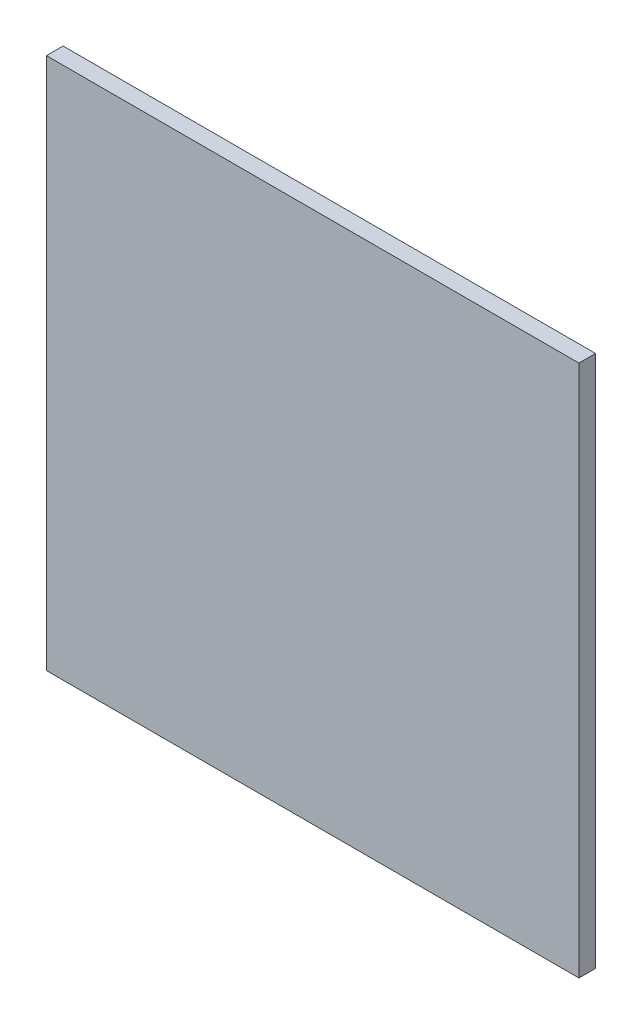
SolidWorks part; units mm, degrees
ref_plane "Alzado" through (0, 0, 0) normal (0, 0, 1) x (1, 0, 0)
ref_plane "Planta" through (0, 0, 0) normal (0, 1, 0) x (1, 0, 0)
ref_plane "Vista lateral" through (0, 0, 0) normal (1, 0, 0) x (0, 0, -1)
sketch "Croquis1" plane through (0, 0, 0) normal (0, 0, 1) x (1, 0, 0)
  line L1 (-210, 110) -> (110, 110)
  line L2 (-210, 110) -> (-210, -210)
  line L3 (-210, -210) -> (110, -210)
  line L4 (110, 110) -> (110, -210)
  point P0 (0, 0)
  dimension "D1" = 110
  dimension "D4" = 110
  dimension "D2" = 320
  dimension "D3" = 320
extrude "Saliente-Extruir2" add sketch "Croquis1" along normal blind 10
sketch "Croquis2" plane through (0, 0, 0) normal (0, 0, 1) x (1, 0, 0)
  line L1 (30, 30) -> (-130, 30)
  line L2 (30, 30) -> (30, -130)
  line L3 (30, -130) -> (-130, -130)
  line L4 (-130, 30) -> (-130, -130)
  line L5 (110, -210) -> (110, 110) construction
  line L6 (-210, -210) -> (110, -210) construction
  point P0 (-55.304, -54.2189)
  point P5 (-50, 30)
  dimension "D1" = 160
  dimension "D2" = 160
  dimension "D3" = 80
  dimension "D4" = 80
extrude "Saliente-Extruir3" add sketch "Croquis2" against normal blind 58
sketch "Croquis3" plane through (0, 0, -58) normal (0, 0, -1) x (-1, 0, 0)
  circle A0 centre (50, -50) radius 19
  dimension "D1" = 38
extrude "Cortar-Extruir1" cut sketch "Croquis3" against normal blind 58
sketch "Croquis6" plane through (0, 0, -58) normal (0, 0, -1) x (-1, 0, 0)
  line L0 (-30, 30) -> (130, 30) construction
  line L1 (-20, 20) -> (120, 20)
  line L2 (-20, 20) -> (-20, -120)
  line L3 (-20, -120) -> (120, -120)
  line L4 (120, 20) -> (120, -120)
  line L5 (130, 30) -> (130, -130) construction
  line L6 (50, -85) -> (101.7276, -85)
  circle A0 centre (50, -50) radius 35
  dimension "D1" = 70
  dimension "D5" = 10
  dimension "D2" = 10
  dimension "D3" = 140
  dimension "D4" = 140
extrude "Cortar-Extruir5" cut sketch "Croquis6" against normal blind 60
sketch "Croquis7" plane through (0, -130, 0) normal (0, -1, 0) x (1, 0, 0)
  line L0 (-210, 0) -> (110, 0) construction
  line L1 (-60, 0) -> (-40, 0)
  line L2 (-60, 0) -> (-60, -10)
  line L3 (-60, -10) -> (-40, -10)
  line L4 (-40, 0) -> (-40, -10)
  line L6 (30, -58) -> (30, 0) construction
  point P8 (-50, 0)
  dimension "D1" = 20
  dimension "D2" = 10
  dimension "D3" = 80
extrude "Cortar-Extruir6" cut sketch "Croquis7" against normal blind 69
